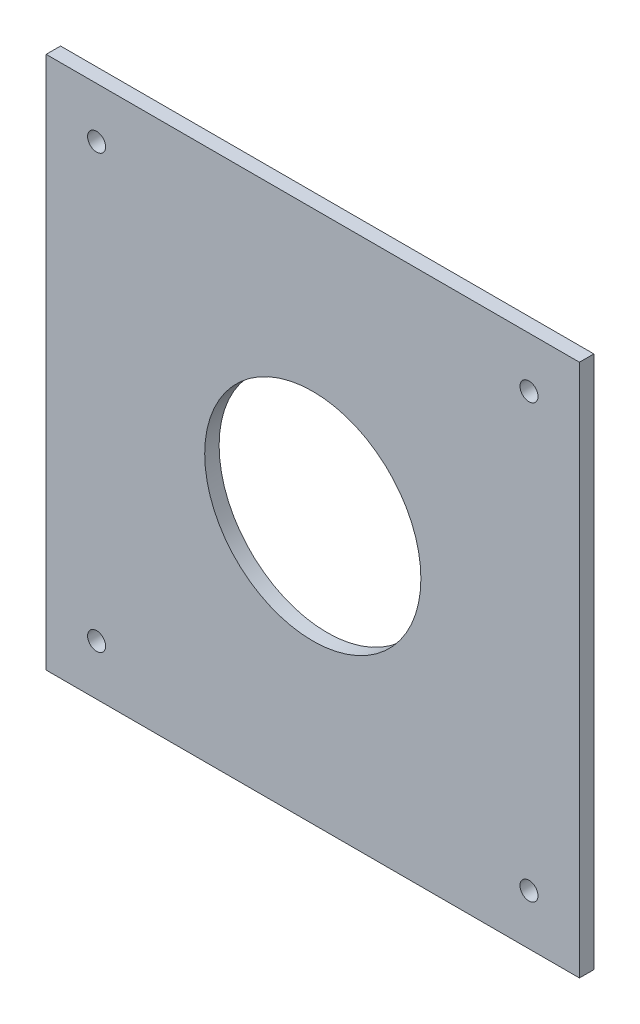
SolidWorks part; units mm, degrees
ref_plane "正面" through (0, 0, 0) normal (0, 0, 1) x (1, 0, 0)
ref_plane "平面" through (0, 0, 0) normal (0, 1, 0) x (1, 0, 0)
ref_plane "右側面" through (0, 0, 0) normal (1, 0, 0) x (0, 0, -1)
sketch "ｽｹｯﾁ1" plane through (0, 0, 0) normal (0, 0, 1) x (1, 0, 0)
  line L1 (0, 0) -> (74, 0)
  line L2 (0, 0) -> (0, 74)
  line L3 (0, 74) -> (74, 74)
  line L4 (74, 0) -> (74, 74)
  dimension "D1" = 74
  dimension "D2" = 74
extrude "ﾎﾞｽ - 押し出し1" add sketch "ｽｹｯﾁ1" along normal blind 2
sketch "ｽｹｯﾁ2" plane through (0, 0, 2) normal (0, 0, 1) x (1, 0, 0)
  line L0 (74, 0) -> (74, 74) construction
  line L1 (74, 74) -> (0, 74) construction
  circle A0 centre (37, 37) radius 15
  dimension "D1" = 30
  dimension "D2" = 37
  dimension "D3" = 37
extrude "ｶｯﾄ - 押し出し1" cut sketch "ｽｹｯﾁ2" against normal blind 2
hole_wizard "M3x0.5 ねじ穴1" positions "ｽｹｯﾁ3" profile "ｽｹｯﾁ4" tap size "M3x0.5" standard "JIS" end condition through all
sketch "ｽｹｯﾁ3" plane through (0, 0, 2) normal (0, 0, 1) x (1, 0, 0)
  line L0 (74, 74) -> (0, 74) construction
  line L1 (0, 74) -> (0, 0) construction
  line L2 (74, 0) -> (74, 74) construction
  point P0 (7, 67)
  point P2 (67, 67)
  dimension "D1" = 7
  dimension "D2" = 7
  dimension "D3" = 7
  dimension "D4" = 7
sketch "ｽｹｯﾁ4" plane through (7, 67, 2) normal (1, 0, 0) x (0, -1, 0)
  line L0 (0, 0) -> (0, 2)
  line L1 (0, 2) -> (1.25, 2)
  line L2 (1.25, 2) -> (1.25, 0)
  line L5 (1.25, 0) -> (0, 0)
  line L11 (0, -6.35) -> (0, 107.95) construction
  dimension "次ｻｰﾌｪｽまでのねじ下穴ﾄﾞﾘﾙ直径" = 2.5
  dimension "次ｻｰﾌｪｽまでのねじ下穴ﾄﾞﾘﾙの深さ" = 2
cosmetic thread "穴のねじ山1" parameters "D2"=3
cosmetic thread "穴のねじ山2" parameters "D2"=3
ref_plane "平面1" through (0, 37, 0) normal (0, 1, 0) x (1, 0, 0)
mirror "ﾐﾗｰ1" about plane through (0, 37, 0) normal (0, 1, 0) of "M3x0.5 ねじ穴1"
